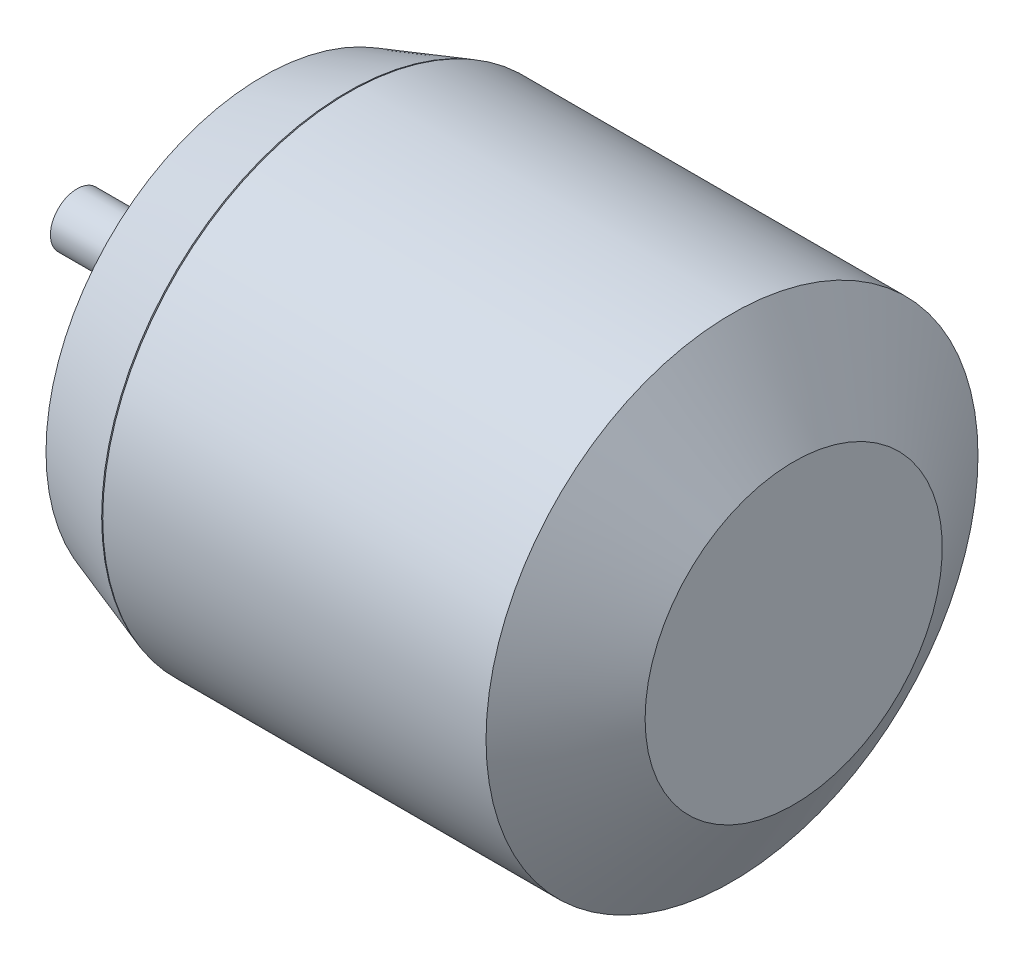
SolidWorks part; units mm, degrees
ref_plane "Front Plane" through (0, 0, 0) normal (0, 0, 1) x (1, 0, 0)
ref_plane "Top Plane" through (0, 0, 0) normal (0, 1, 0) x (1, 0, 0)
ref_plane "Right Plane" through (0, 0, 0) normal (1, 0, 0) x (0, 0, -1)
sketch "Sketch1" plane through (0, 0, 0) normal (0, 0, 1) x (1, 0, 0)
  line L0 (-72.5045, 0) -> (67.4398, 0) construction
  line L1 (-30, 12.25) -> (-30, 1.5)
  line L2 (-30, 12.25) -> (-25.1452, 13.9)
  line L3 (-25.1452, 13.9) -> (-25.1452, 6.9)
  line L4 (-25.1452, 6.9) -> (-25.2361, 6.8584)
  line L5 (-25.2361, 6.8584) -> (-25.2361, 13.9)
  line L6 (-25.2361, 13.9) -> (-3.485, 13.9)
  line L9 (-3.485, 13.9) -> (0, 8.3964)
  line L10 (0, 8.3964) -> (0, 0)
  line L11 (-30, 1.5) -> (-40.5, 1.5)
  line L12 (-40.5, 1.5) -> (-40.5, 0)
  line L13 (-40.5, 0) -> (0, 0)
  point P4 (0, 0)
  point P10 (-30, 13)
  point P11 (-25.9059, 13.9)
  dimension "D1" = 30
  dimension "D2" = 27.8
  dimension "D3" = 0.1
  dimension "D4" = 24.5
  dimension "D5" = 7
  dimension "D6" = 3
  dimension "D7" = 10.5
revolve "Revolve2" add sketch "Sketch1" angle 360 about L0
sketch "Sketch2" plane through (-30, 0, 0) normal (-1, 0, 0) x (0, 0, 1)
  line L0 (0, 0) -> (10.2702, 12.8953) construction
  line L1 (0, 0) -> (-15.3823, 12.251) construction
  circle A0 centre (5.9184, 7.4312) radius 1.5
  circle A1 centre (-6.2578, 4.9839) radius 1.5
  circle A2 centre (6.2578, -4.9839) radius 1.5
  circle A3 centre (-5.9184, -7.4312) radius 1.5
  dimension "D3" = 3
  dimension "D1" = 90
  dimension "D2" = 9.5
  dimension "D4" = 8
extrude "Cut-Extrude1" cut sketch "Sketch2" against normal blind 10
